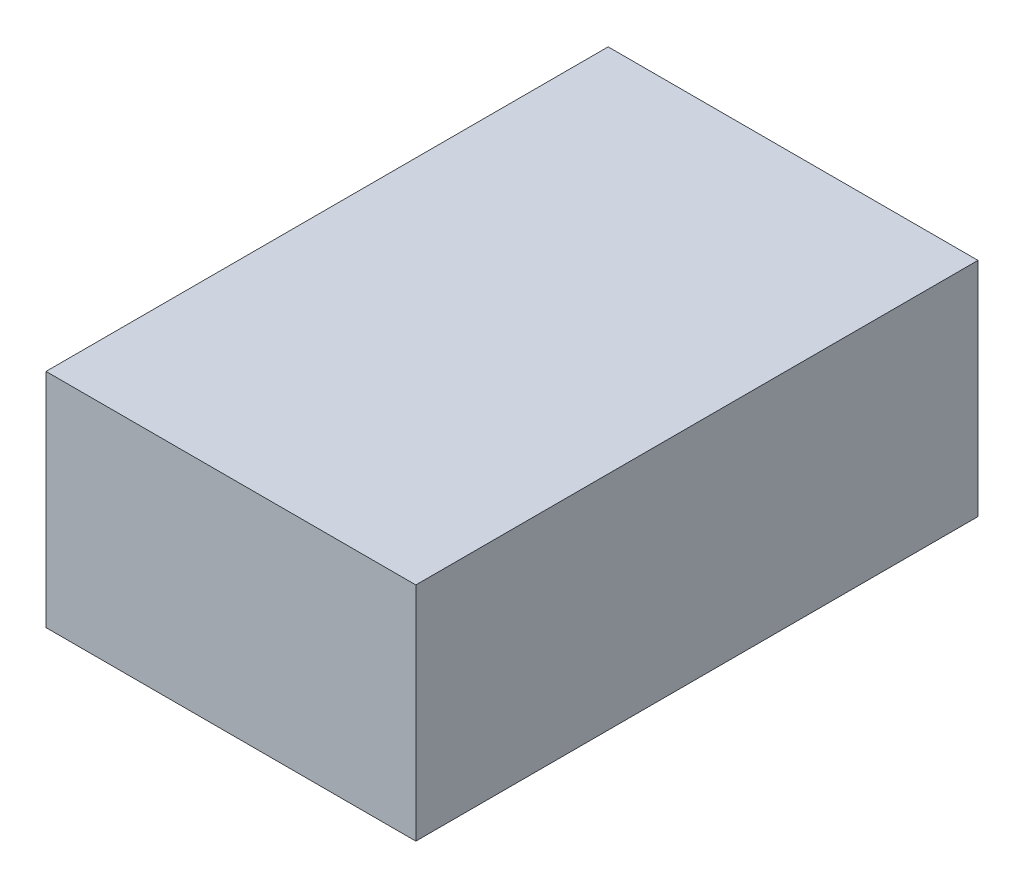
SolidWorks part; units mm, degrees
ref_plane "Front Plane" through (0, 0, 0) normal (0, 0, 1) x (1, 0, 0)
ref_plane "Top Plane" through (0, 0, 0) normal (0, 1, 0) x (1, 0, 0)
ref_plane "Right Plane" through (0, 0, 0) normal (1, 0, 0) x (0, 0, -1)
sketch "Sketch1" plane through (0, 0, 0) normal (0, 1, 0) x (1, 0, 0)
  line L1 (0, 0) -> (63.5, 0)
  line L2 (0, 0) -> (0, 96.52)
  line L3 (0, 96.52) -> (63.5, 96.52)
  line L4 (63.5, 0) -> (63.5, 96.52)
  dimension "D1" = 63.5
  dimension "D2" = 96.52
extrude "Boss-Extrude1" add sketch "Sketch1" along normal blind 38.1
